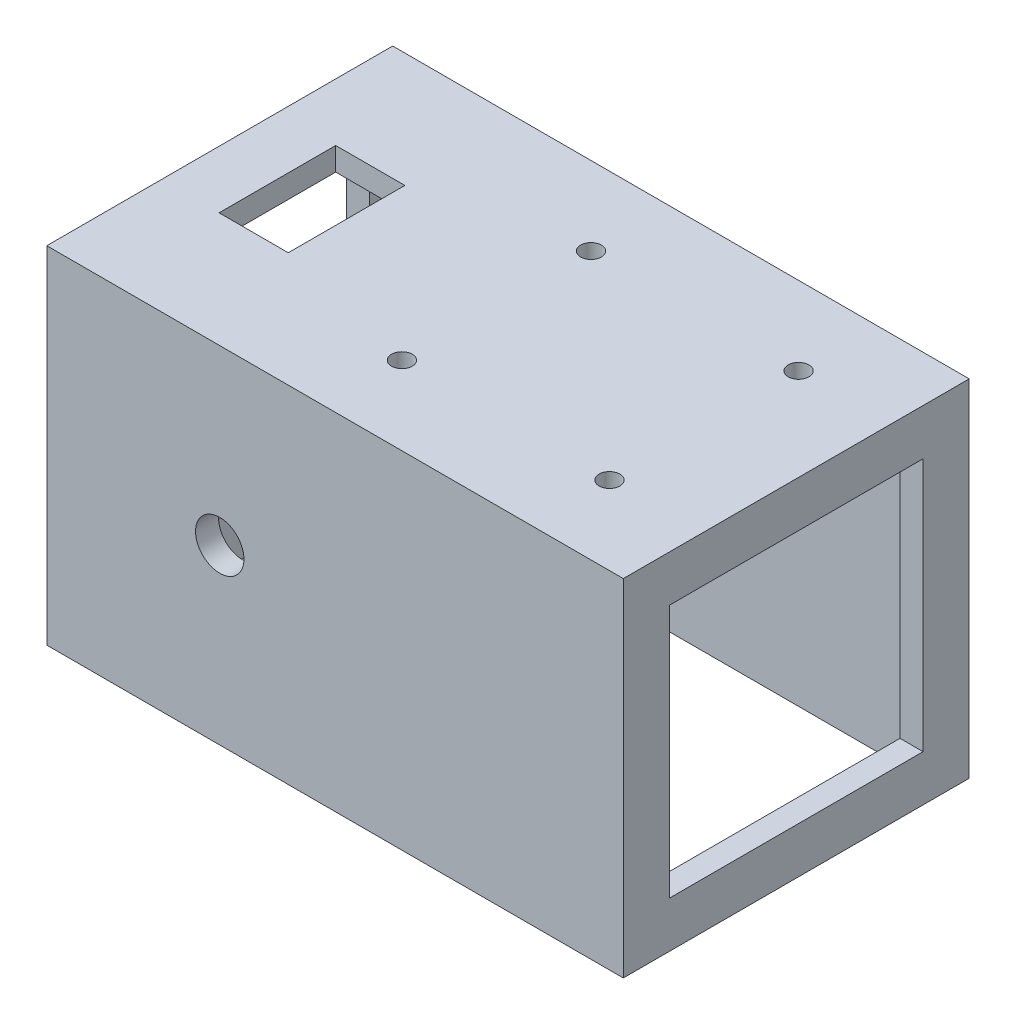
SolidWorks part; units mm, degrees
ref_plane "Front Plane" through (0, 0, 0) normal (0, 0, 1) x (1, 0, 0)
ref_plane "Top Plane" through (0, 0, 0) normal (0, 1, 0) x (1, 0, 0)
ref_plane "Right Plane" through (0, 0, 0) normal (1, 0, 0) x (0, 0, -1)
sketch "Sketch1" plane through (0, 0, 0) normal (0, 0, 1) x (1, 0, 0)
  line L1 (-31.75, 19.05) -> (31.75, 19.05)
  line L2 (-31.75, 19.05) -> (-31.75, -19.05)
  line L3 (-31.75, -19.05) -> (31.75, -19.05)
  line L4 (31.75, 19.05) -> (31.75, -19.05)
  line L5 (-31.75, 19.05) -> (31.75, -19.05) construction
  line L6 (-31.75, -19.05) -> (31.75, 19.05) construction
  point P0 (0, 0)
  dimension "D1" = 63.5
  dimension "D2" = 38.1
extrude "Boss-Extrude1" add sketch "Sketch1" along normal mid plane 38.1
shell "Shell1" thickness 2.54
sketch "Sketch2" plane through (0, 19.05, 0) normal (0, 1, 0) x (1, 0, 0)
  line L5 (21.59, 10.414) -> (-1.27, 10.414) construction
  line L6 (21.59, 10.414) -> (21.59, -10.414) construction
  line L7 (21.59, -10.414) -> (-1.27, -10.414) construction
  line L8 (-1.27, 10.414) -> (-1.27, -10.414) construction
  line L9 (21.59, 10.414) -> (-1.27, -10.414) construction
  line L10 (21.59, -10.414) -> (-1.27, 10.414) construction
  line L11 (31.75, -19.05) -> (31.75, 19.05) construction
  circle A0 centre (-1.27, 10.414) radius 1.143
  circle A1 centre (21.59, 10.414) radius 1.143
  circle A2 centre (21.59, -10.414) radius 1.143
  circle A3 centre (-1.27, -10.414) radius 1.143
  point P0 (10.16, 0)
  dimension "D4" = 2.286
  dimension "D1" = 20.828
  dimension "D2" = 22.86
  dimension "D3" = 10.16
extrude "Cut-Extrude1" cut sketch "Sketch2" against normal through all
sketch "Sketch4" plane through (0, 19.05, 0) normal (0, 1, 0) x (1, 0, 0)
  line L0 (-31.75, -19.05) -> (-31.75, 19.05) construction
  line L1 (-17.78, 6.4211) -> (-25.4, 6.4211)
  line L2 (-17.78, 6.4211) -> (-17.78, -6.4211)
  line L3 (-17.78, -6.4211) -> (-25.4, -6.4211)
  line L4 (-25.4, 6.4211) -> (-25.4, -6.4211)
  line L5 (-17.78, 6.4211) -> (-25.4, -6.4211) construction
  line L6 (-17.78, -6.4211) -> (-25.4, 6.4211) construction
  point P0 (-21.59, 0)
  dimension "D1" = 6.35
  dimension "D2" = 7.62
extrude "Cut-Extrude2" cut sketch "Sketch4" against normal through all
sketch "Sketch5" plane through (0, 0, 19.05) normal (0, 0, 1) x (1, 0, 0)
  circle A0 centre (-12.7, 0) radius 2.667
  dimension "D1" = 5.334
  dimension "D2" = 5.08
extrude "Cut-Extrude3" cut sketch "Sketch5" against normal through all
sketch "Sketch6" plane through (-31.75, 0, 0) normal (-1, 0, 0) x (0, 0, 1)
  line L0 (-19.05, 19.05) -> (-19.05, -19.05) construction
  line L1 (-13.97, 13.97) -> (13.97, 13.97)
  line L2 (-13.97, 13.97) -> (-13.97, -13.97)
  line L3 (-13.97, -13.97) -> (13.97, -13.97)
  line L4 (13.97, 13.97) -> (13.97, -13.97)
  line L5 (19.05, 19.05) -> (19.05, -19.05) construction
  line L6 (19.05, 19.05) -> (-19.05, 19.05) construction
  line L7 (19.05, -19.05) -> (-19.05, -19.05) construction
  dimension "D1" = 5.08
  dimension "D2" = 5.08
  dimension "D3" = 5.08
  dimension "D4" = 5.08
extrude "Cut-Extrude4" cut sketch "Sketch6" against normal through all
equation "\"D2@Sketch6\"=\"D1@Sketch6\""
equation "\"D3@Sketch6\"=\"D1@Sketch6\""
equation "\"D4@Sketch6\"=\"D1@Sketch6\""
